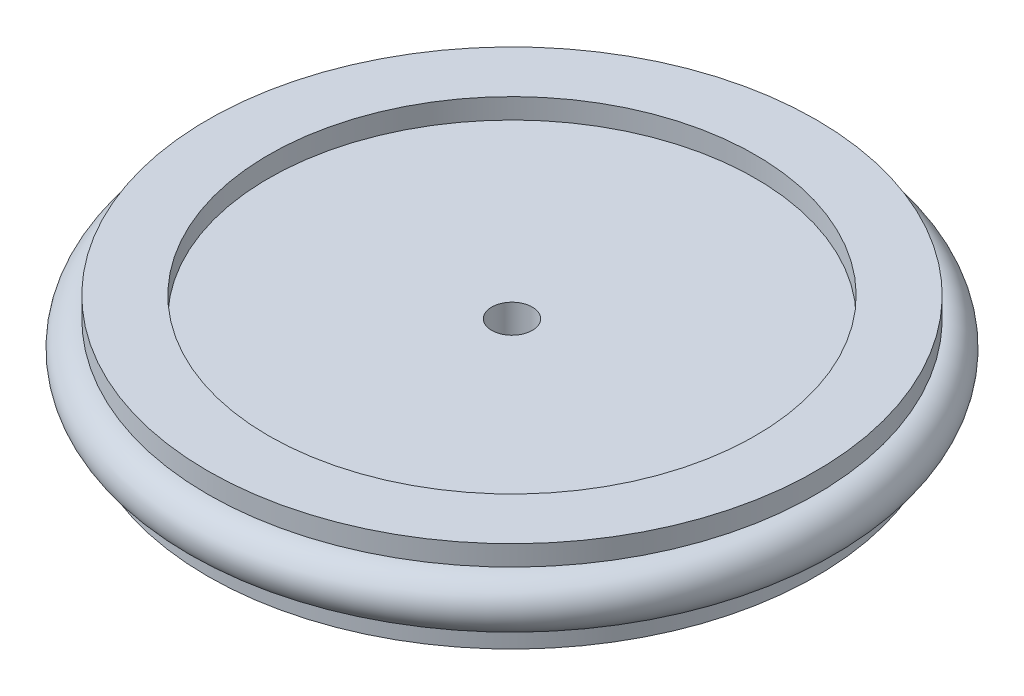
SolidWorks part; units mm, degrees
ref_plane "Front Plane" through (0, 0, 0) normal (0, 0, 1) x (1, 0, 0)
ref_plane "Top Plane" through (0, 0, 0) normal (0, 1, 0) x (1, 0, 0)
ref_plane "Right Plane" through (0, 0, 0) normal (1, 0, 0) x (0, 0, -1)
sketch "Sketch1" plane through (0, 0, 0) normal (0, 0, 1) x (1, 0, 0)
  line L0 (0, 26.3538) -> (0, -25.8305) construction
  line L1 (-45.5304, 0) -> (43.138, 0) construction
  line L2 (1, -2) -> (1, 2.5)
  line L3 (1, -2) -> (3, -2)
  line L4 (3, -2) -> (3, 0)
  line L5 (3, 0) -> (12, 0)
  line L6 (12, 0) -> (12, -1)
  line L7 (12, -1) -> (15, -1)
  line L8 (15, 3.5) -> (15, 2.5)
  line L9 (15, -1) -> (15, 0)
  line L11 (15, 3.5) -> (12, 3.5)
  line L12 (12, 3.5) -> (12, 2.5)
  line L13 (12, 2.5) -> (1, 2.5)
  arc A0 (15, 0) -> (15, 2.5) centre (15, 1.25) ccw
  dimension "D1" = 1
  dimension "D2" = 2
  dimension "D9" = 1
  dimension "D3" = 2
  dimension "D4" = 11
  dimension "D5" = 3
  dimension "D6" = 4.5
  dimension "D10" = 9
  dimension "D11" = 1
revolve "Revolve1" add sketch "Sketch1" angle 360 about L0
